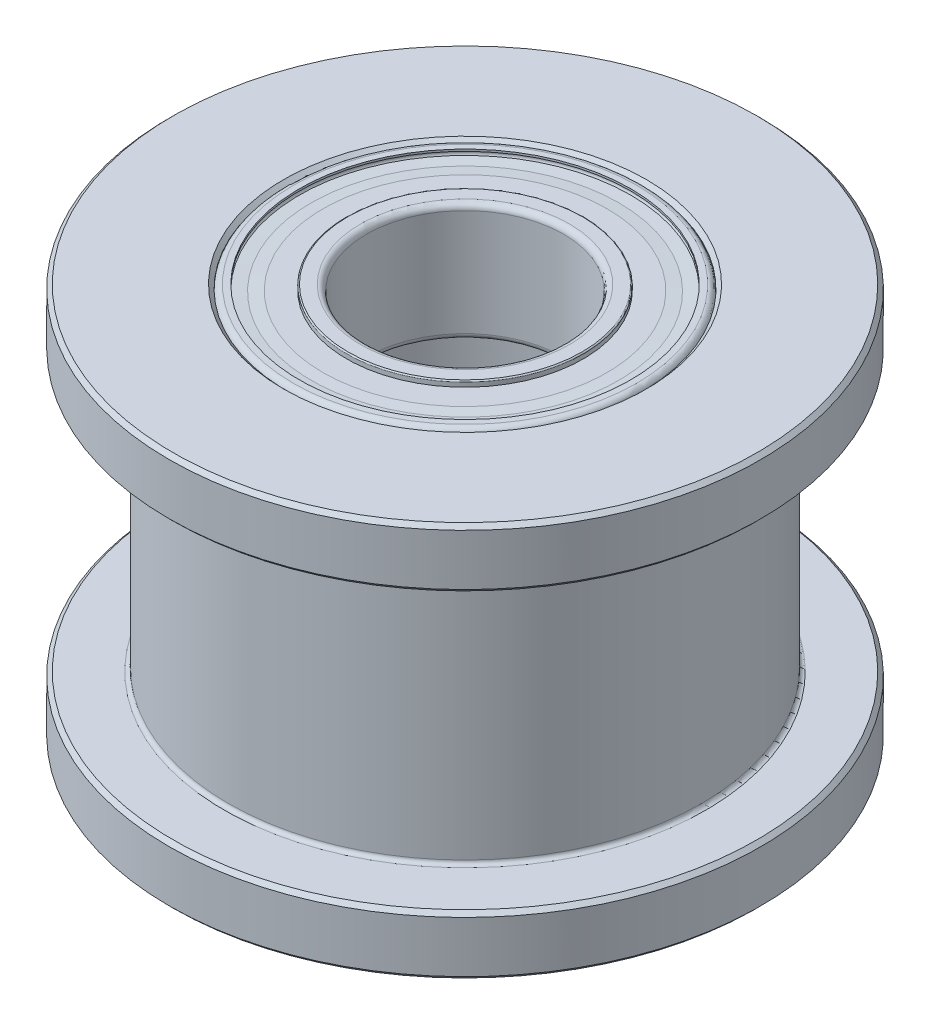
SolidWorks part; units mm, degrees
material "6061-T6 (SS)"
ref_plane "Přední rovina" through (0, 0, 0) normal (0, 0, 1) x (1, 0, 0)
ref_plane "Horní rovina" through (0, 0, 0) normal (0, 1, 0) x (1, 0, 0)
ref_plane "Pravá rovina" through (0, 0, 0) normal (1, 0, 0) x (0, 0, -1)
sketch "Skica1" plane through (0, 0, 0) normal (0, 0, 1) x (1, 0, 0)
  line L0 (4.5, 10) -> (7.5, 10)
  line L1 (7.5, 10) -> (7.5, 8.5)
  line L2 (7.5, 8.5) -> (6, 8.5)
  line L3 (6, 8.5) -> (6, 1.5)
  line L4 (6, 1.5) -> (7.5, 1.5)
  line L5 (7.5, 1.5) -> (7.5, 0)
  line L6 (7.5, 0) -> (4.5, 0)
  line L8 (4.5, 10) -> (4.5, 7)
  line L9 (4.5, 7) -> (3.5, 7)
  line L10 (3.5, 7) -> (3.5, 3)
  line L11 (3.5, 3) -> (4.5, 3)
  line L12 (4.5, 3) -> (4.5, 0)
  line L13 (0, 0) -> (0, -4.1646) construction
  dimension "D1" = 1.5
  dimension "D2" = 7
  dimension "D3" = 4.5
  dimension "D4" = 3.5
  dimension "D5" = 6
  dimension "D6" = 3
  dimension "D7" = 7.5
revolve "Rotovat1" add sketch "Skica1" angle 360 about L13
chamfer "Zkosení1" distance 0.1 angle 45 8 edges at (0, 3, 3.5) (0, 0, 4.5) (0, 7, 3.5) (0, 0, 7.5) (0, 1.5, 7.5) (0, 8.5, 7.5) (0, 10, 7.5) (0, 10, 4.5)
fillet "Zaoblit1" radius 0.1 4 edges at (0, 3, 4.5) (0, 1.5, 6) (0, 8.5, 6) (0, 7, 4.5)
sketch "Skica4" plane through (0, 0, 0) normal (0, 0, 1) x (1, 0, 0)
  line L0 (4.5, 9.85) -> (4.5, 7.15)
  line L1 (4.35, 7) -> (4.2, 7)
  line L2 (4.2, 7) -> (4.2, 7.05)
  line L3 (3.85, 7.2828) -> (4.2132, 7.229)
  line L4 (3.85, 7.2828) -> (3.85, 8.0528)
  line L5 (3.85, 8.9472) -> (3.85, 9.7172)
  line L6 (3.85, 9.7172) -> (4.2132, 9.771)
  line L7 (4.35, 10) -> (4.2, 10)
  line L8 (4.2, 10) -> (4.2, 9.95)
  line L9 (0, 0) -> (0, 18.4294) construction
  line L10 (4.4, 7) -> (-4.4, 7) construction
  arc A0 (4.35, 10) -> (4.5, 9.85) centre (4.35, 9.85) cw
  arc A1 (4.35, 7) -> (4.5, 7.15) centre (4.35, 7.15) ccw
  arc A2 (4.2, 9.95) -> (4.2132, 9.771) centre (4.2, 9.86) cw
  arc A3 (3.85, 8.9472) -> (3.85, 8.0528) centre (3.45, 8.5) cw
  arc A4 (4.2, 7.05) -> (4.2132, 7.229) centre (4.2, 7.14) ccw
  point P26 (4.5, 8.5)
  point P29 (4.275, 7)
  dimension "D3" = 0.09
  dimension "D6" = 0.15
  dimension "D7" = 0.6
  dimension "D1" = 4.5
  dimension "D2" = 3.85
  dimension "D4" = 0.05
  dimension "D5" = 0.15
  dimension "D8" = 0.77
  dimension "D9" = 3
  dimension "D10" = 1.05
revolve "Rotovat2" add sketch "Skica4" angle 360 about L9
sketch "Skica5" plane through (0, 0, 0) normal (0, 0, 1) x (1, 0, 0)
  line L0 (2.5, 9.85) -> (2.5, 7.15)
  line L1 (2.65, 10) -> (2.97, 10)
  line L2 (3, 9.97) -> (3, 9.86)
  line L3 (3, 9.86) -> (3.6, 9.86)
  line L4 (3.6, 9.86) -> (3.9, 9.84)
  line L5 (3.9, 9.84) -> (4.2, 9.86)
  line L6 (4.2, 9.86) -> (4.2, 9.81)
  line L7 (4.2, 9.81) -> (3.9, 9.77)
  line L8 (3.9, 9.77) -> (3.6, 9.77)
  line L9 (3.6, 9.77) -> (3, 9.81)
  line L10 (3, 9.81) -> (3, 8.8969)
  line L11 (2.65, 7) -> (2.97, 7)
  line L12 (0, 0) -> (0, 20.363) construction
  line L13 (3, 7.03) -> (3, 7.14)
  line L21 (3, 7.19) -> (3, 8.1031)
  line L22 (3, 7.14) -> (3.6, 7.14)
  line L23 (3.6, 7.14) -> (3.8962, 7.1917)
  line L24 (3.8962, 7.1917) -> (4.1924, 7.14)
  line L25 (4.1924, 7.14) -> (4.1924, 7.19)
  line L26 (4.1924, 7.19) -> (3.8975, 7.2581)
  line L27 (3.8975, 7.2581) -> (3.5975, 7.2581)
  line L28 (3.5975, 7.2581) -> (3, 7.19)
  line L29 (-4.2, 7) -> (4.2, 7) construction
  arc A0 (2.65, 7) -> (2.5, 7.15) centre (2.65, 7.15) cw
  arc A1 (2.65, 10) -> (2.5, 9.85) centre (2.65, 9.85) ccw
  arc A2 (3, 9.97) -> (2.97, 10) centre (2.97, 9.97) ccw
  arc A3 (3, 7.03) -> (2.97, 7) centre (2.97, 7.03) cw
  arc A4 (3, 8.8969) -> (3, 8.1031) centre (3.45, 8.5) ccw
  dimension "D3" = 0.15
  dimension "D4" = 0.11
  dimension "D5" = 0.03
  dimension "D7" = 0.6
  dimension "D1" = 2.5
  dimension "D2" = 3
  dimension "D6" = 0.6
  dimension "D8" = 0.95
  dimension "D9" = 3
  dimension "D10" = 1.2
  dimension "D11" = 0.3
  dimension "D12" = 0.05
  dimension "D13" = 0.9
  dimension "D14" = 0.6
  dimension "D15" = 0.09
  dimension "D16" = 0.05
  dimension "D17" = 0.05
revolve "Rotovat3" add sketch "Skica5" angle 360 about L12
sketch "Skica6" plane through (0, 0, 0) normal (0, 0, 1) x (1, 0, 0)
  line L0 (3.45, 9.1) -> (3.45, 7.9)
  line L4 (-4.2, 7) -> (4.2, 7) construction
  arc A0 (3.45, 9.1) -> (3.45, 7.9) centre (3.45, 8.5) cw
  dimension "D1" = 0.6
  dimension "D2" = 1.5
  dimension "D3" = 3.45
revolve "Rotovat4" add sketch "Skica6" angle 360 about L0
pattern_circular "Kruhové pole1" count 8 over 360 about axis through (0, 0, 0) along (0, 1, 0) of bodies 105
sketch "Skica7" plane through (0, 0, 0) normal (0, 0, 1) x (1, 0, 0)
  line L0 (4.5, 2.85) -> (4.5, 0.15)
  line L1 (4.35, 0) -> (4.2, 0)
  line L2 (4.2, 0) -> (4.2, 0.05)
  line L3 (3.85, 0.2828) -> (4.2132, 0.229)
  line L4 (3.85, 0.2828) -> (3.85, 1.0528)
  line L5 (3.85, 1.9472) -> (3.85, 2.7172)
  line L6 (3.85, 2.7172) -> (4.2132, 2.771)
  line L7 (4.35, 3) -> (4.2, 3)
  line L8 (4.2, 3) -> (4.2, 2.95)
  line L9 (0, 0) -> (0, 11.2374) construction
  arc A0 (4.35, 3) -> (4.5, 2.85) centre (4.35, 2.85) cw
  arc A1 (4.35, 0) -> (4.5, 0.15) centre (4.35, 0.15) ccw
  arc A2 (4.2, 2.95) -> (4.2132, 2.771) centre (4.2, 2.86) cw
  arc A3 (3.85, 1.9472) -> (3.85, 1.0528) centre (3.45, 1.5) cw
  arc A4 (4.2, 0.05) -> (4.2132, 0.229) centre (4.2, 0.14) ccw
  point P19 (4.5, 1.5)
  point P20 (4.275, 0)
  dimension "D1" = 0.09
  dimension "D4" = 0.15
  dimension "D5" = 0.6
  dimension "D2" = 0.05
  dimension "D3" = 0.15
  dimension "D6" = 0.77
  dimension "D7" = 3
  dimension "D8" = 1.05
  dimension "D9" = 4.5
  dimension "D10" = 3.85
revolve "Rotovat5" add sketch "Skica7" angle 360 about L9
sketch "Skica8" plane through (0, 0, 0) normal (0, 0, 1) x (1, 0, 0)
  line L0 (2.5, 2.85) -> (2.5, 0.15)
  line L1 (2.65, 3) -> (2.97, 3)
  line L2 (3, 2.97) -> (3, 2.86)
  line L3 (3, 2.86) -> (3.6, 2.86)
  line L4 (3.6, 2.86) -> (3.9, 2.84)
  line L5 (3.9, 2.84) -> (4.2, 2.86)
  line L6 (4.2, 2.86) -> (4.2, 2.81)
  line L7 (4.2, 2.81) -> (3.9, 2.77)
  line L8 (3.9, 2.77) -> (3.6, 2.77)
  line L9 (3.6, 2.77) -> (3, 2.81)
  line L10 (3, 2.81) -> (3, 1.8969)
  line L11 (2.65, 0) -> (2.97, 0)
  line L12 (3, 0.03) -> (3, 0.14)
  line L13 (3, 0.19) -> (3, 1.1031)
  line L14 (3, 0.14) -> (3.6, 0.14)
  line L15 (3.6, 0.14) -> (3.8962, 0.1917)
  line L16 (3.8962, 0.1917) -> (4.1924, 0.14)
  line L17 (4.1924, 0.14) -> (4.1924, 0.19)
  line L18 (4.1924, 0.19) -> (3.8975, 0.2581)
  line L19 (3.8975, 0.2581) -> (3.5975, 0.2581)
  line L20 (3.5975, 0.2581) -> (3, 0.19)
  line L21 (0, 0) -> (0, -2.9362) construction
  arc A0 (2.65, 0) -> (2.5, 0.15) centre (2.65, 0.15) cw
  arc A1 (2.65, 3) -> (2.5, 2.85) centre (2.65, 2.85) ccw
  arc A2 (3, 2.97) -> (2.97, 3) centre (2.97, 2.97) ccw
  arc A3 (3, 0.03) -> (2.97, 0) centre (2.97, 0.03) cw
  arc A4 (3, 1.8969) -> (3, 1.1031) centre (3.45, 1.5) ccw
  dimension "D1" = 0.15
  dimension "D2" = 0.03
  dimension "D5" = 0.6
  dimension "D3" = 0.11
  dimension "D4" = 0.6
  dimension "D6" = 0.95
  dimension "D7" = 3
  dimension "D8" = 1.2
  dimension "D9" = 0.3
  dimension "D10" = 0.05
  dimension "D11" = 0.9
  dimension "D12" = 0.6
  dimension "D13" = 0.09
  dimension "D14" = 0.05
  dimension "D15" = 0.05
  dimension "D16" = 2.5
  dimension "D17" = 3
revolve "Rotovat6" add sketch "Skica8" angle 360 about L21
sketch "Skica9" plane through (0, 0, 0) normal (0, 0, 1) x (1, 0, 0)
  line L0 (3.45, 2.1) -> (3.45, 0.9)
  line L1 (0, -2.351) -> (0, 5.6956) construction
  arc A0 (3.45, 2.1) -> (3.45, 0.9) centre (3.45, 1.5) cw
  dimension "D1" = 0.6
  dimension "D2" = 3.45
  dimension "D3" = 1.5
revolve "Rotovat7" add sketch "Skica9" angle 360 about L0
pattern_circular "Kruhové pole3" count 8 over 360 about axis through (0, 0, 0) along (0, 1, 0) of bodies 123
